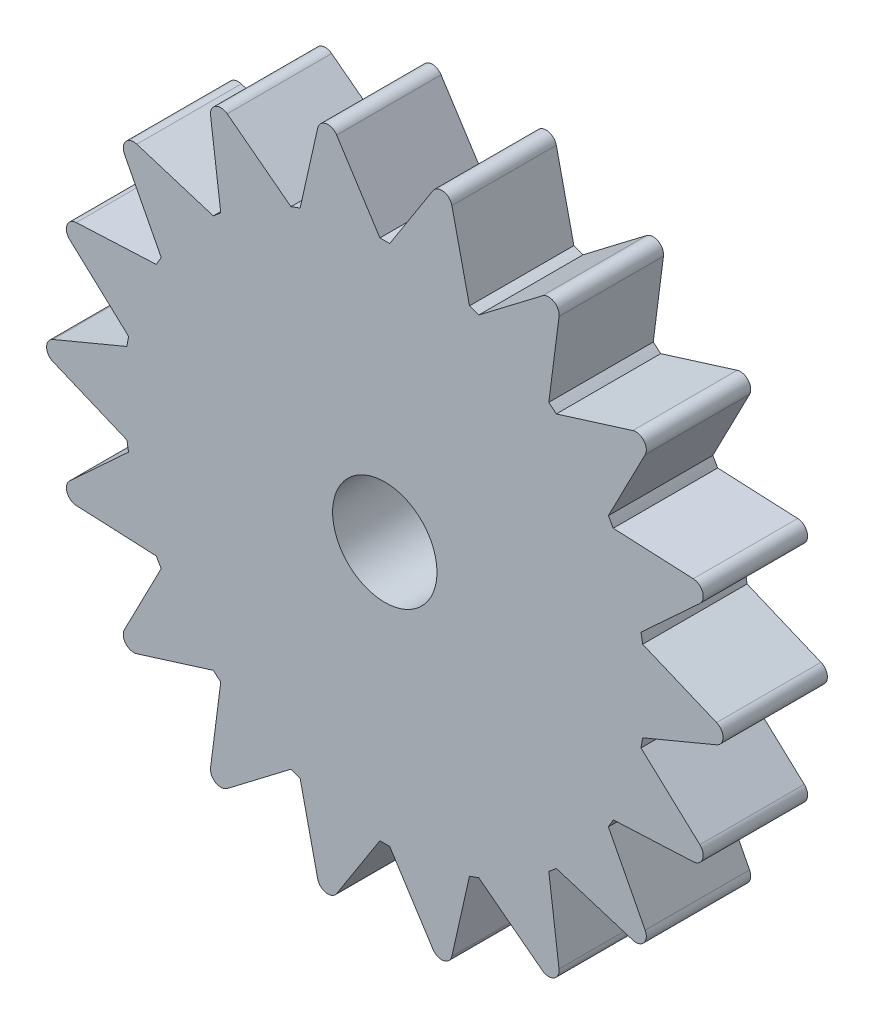
SolidWorks part; units mm, degrees
ref_plane "前基準面" through (0, 0, 0) normal (0, 0, 1) x (1, 0, 0)
ref_plane "上基準面" through (0, 0, 0) normal (0, 1, 0) x (1, 0, 0)
ref_plane "右基準面" through (0, 0, 0) normal (1, 0, 0) x (0, 0, -1)
sketch "草圖1" plane through (0, 0, 0) normal (0, 0, 1) x (1, 0, 0)
  line L0 (0, 0) -> (-77.5811, 0) construction
  line L1 (-63.549, 1.8454) -> (-49.3944, 7.7587)
  line L2 (-63.549, -1.8454) -> (-49.3944, -7.7587)
  line L3 (-60.3477, 20.0009) -> (-49.0691, 9.6031)
  line L4 (-59.0853, 23.4692) -> (-43.7619, 24.1847)
  line L5 (-49.8676, 39.4348) -> (-42.8255, 25.8066)
  line L6 (-47.4951, 42.2622) -> (-32.8511, 37.6936)
  line L7 (-33.3727, 54.1123) -> (-31.4164, 38.8974)
  line L8 (-30.1763, 55.9578) -> (-17.9779, 46.6561)
  line L9 (-12.8526, 62.2631) -> (-16.2181, 47.2967)
  line L10 (-9.2178, 62.904) -> (-0.9364, 49.9912)
  line L11 (9.2178, 62.904) -> (0.9364, 49.9912)
  line L12 (12.8526, 62.2631) -> (16.2181, 47.2967)
  line L13 (30.1763, 55.9578) -> (17.9779, 46.6561)
  line L14 (33.3727, 54.1123) -> (31.4164, 38.8974)
  line L15 (47.4951, 42.2622) -> (32.8511, 37.6936)
  line L16 (49.8676, 39.4348) -> (42.8255, 25.8066)
  line L17 (59.0853, 23.4692) -> (43.7619, 24.1847)
  line L18 (60.3477, 20.0009) -> (49.0691, 9.6031)
  line L19 (63.549, 1.8454) -> (49.3944, 7.7587)
  line L20 (63.549, -1.8454) -> (49.3944, -7.7587)
  line L21 (60.3477, -20.0009) -> (49.0691, -9.6031)
  line L22 (59.0853, -23.4692) -> (43.7619, -24.1847)
  line L23 (49.8676, -39.4348) -> (42.8255, -25.8066)
  line L24 (47.4951, -42.2622) -> (32.8511, -37.6936)
  line L25 (33.3727, -54.1123) -> (31.4164, -38.8974)
  line L26 (30.1763, -55.9578) -> (17.9779, -46.6561)
  line L27 (12.8526, -62.2631) -> (16.2181, -47.2967)
  line L28 (9.2178, -62.904) -> (0.9364, -49.9912)
  line L29 (-9.2178, -62.904) -> (-0.9364, -49.9912)
  line L30 (-12.8526, -62.2631) -> (-16.2181, -47.2967)
  line L31 (-30.1763, -55.9578) -> (-17.9779, -46.6561)
  line L32 (-33.3727, -54.1123) -> (-31.4164, -38.8974)
  line L33 (-47.4951, -42.2622) -> (-32.8511, -37.6936)
  line L34 (-49.8676, -39.4348) -> (-42.8255, -25.8066)
  line L35 (-59.0853, -23.4692) -> (-43.7619, -24.1847)
  line L36 (-60.3477, -20.0009) -> (-49.0691, -9.6031)
  arc A0 (-49.3944, -7.7587) -> (-49.0691, -9.6031) centre (0, 0) ccw
  arc A1 (-63.549, 1.8454) -> (-63.549, -1.8454) centre (-62.778, 0) ccw
  arc A2 (-59.0853, 23.4692) -> (-60.3477, 20.0009) centre (-58.9921, 21.4714) ccw
  arc A3 (-47.4951, 42.2622) -> (-49.8676, 39.4348) centre (-48.0908, 40.3529) ccw
  arc A4 (-30.1763, 55.9578) -> (-33.3727, 54.1123) centre (-31.389, 54.3674) ccw
  arc A5 (-9.2178, 62.904) -> (-12.8526, 62.2631) centre (-10.9013, 61.8243) ccw
  arc A6 (12.8526, 62.2631) -> (9.2178, 62.904) centre (10.9013, 61.8243) ccw
  arc A7 (33.3727, 54.1123) -> (30.1763, 55.9578) centre (31.389, 54.3674) ccw
  arc A8 (49.8676, 39.4348) -> (47.4951, 42.2622) centre (48.0908, 40.3529) ccw
  arc A9 (60.3477, 20.0009) -> (59.0853, 23.4692) centre (58.9921, 21.4714) ccw
  arc A10 (63.549, -1.8454) -> (63.549, 1.8454) centre (62.778, 0) ccw
  arc A11 (59.0853, -23.4692) -> (60.3477, -20.0009) centre (58.9921, -21.4714) ccw
  arc A12 (47.4951, -42.2622) -> (49.8676, -39.4348) centre (48.0908, -40.3529) ccw
  arc A13 (30.1763, -55.9578) -> (33.3727, -54.1123) centre (31.389, -54.3674) ccw
  arc A14 (9.2178, -62.904) -> (12.8526, -62.2631) centre (10.9013, -61.8243) ccw
  arc A15 (-12.8526, -62.2631) -> (-9.2178, -62.904) centre (-10.9013, -61.8243) ccw
  arc A16 (-33.3727, -54.1123) -> (-30.1763, -55.9578) centre (-31.389, -54.3674) ccw
  arc A17 (-49.8676, -39.4348) -> (-47.4951, -42.2622) centre (-48.0908, -40.3529) ccw
  arc A18 (-60.3477, -20.0009) -> (-59.0853, -23.4692) centre (-58.9921, -21.4714) ccw
  arc A19 (-49.0691, 9.6031) -> (-49.3944, 7.7587) centre (0, 0) ccw
  arc A20 (-42.8255, 25.8066) -> (-43.7619, 24.1847) centre (0, 0) ccw
  arc A21 (-31.4164, 38.8974) -> (-32.8511, 37.6936) centre (0, 0) ccw
  arc A22 (-16.2181, 47.2967) -> (-17.9779, 46.6561) centre (0, 0) ccw
  arc A23 (0.9364, 49.9912) -> (-0.9364, 49.9912) centre (0, 0) ccw
  arc A24 (17.9779, 46.6561) -> (16.2181, 47.2967) centre (0, 0) ccw
  arc A25 (32.8511, 37.6936) -> (31.4164, 38.8974) centre (0, 0) ccw
  arc A26 (43.7619, 24.1847) -> (42.8255, 25.8066) centre (0, 0) ccw
  arc A27 (49.3944, 7.7587) -> (49.0691, 9.6031) centre (0, 0) ccw
  arc A28 (49.0691, -9.6031) -> (49.3944, -7.7587) centre (0, 0) ccw
  arc A29 (42.8255, -25.8066) -> (43.7619, -24.1847) centre (0, 0) ccw
  arc A30 (31.4164, -38.8974) -> (32.8511, -37.6936) centre (0, 0) ccw
  arc A31 (16.2181, -47.2967) -> (17.9779, -46.6561) centre (0, 0) ccw
  arc A32 (-0.9364, -49.9912) -> (0.9364, -49.9912) centre (0, 0) ccw
  arc A33 (-17.9779, -46.6561) -> (-16.2181, -47.2967) centre (0, 0) ccw
  arc A34 (-32.8511, -37.6936) -> (-31.4164, -38.8974) centre (0, 0) ccw
  arc A35 (-43.7619, -24.1847) -> (-42.8255, -25.8066) centre (0, 0) ccw
  point P8 (-67.9664, 0)
  point P97 (0, 0)
  dimension "D1" = 100
  dimension "D2" = 2
  dimension "D3" = 18
extrude "填料-伸長1" add sketch "草圖1" along normal blind 20
sketch "草圖2" plane through (0, 0, 20) normal (0, 0, 1) x (1, 0, 0)
  circle A0 centre (0, 0) radius 10
  dimension "D1" = 20
extrude "除料-伸長1" cut sketch "草圖2" against normal blind 20
